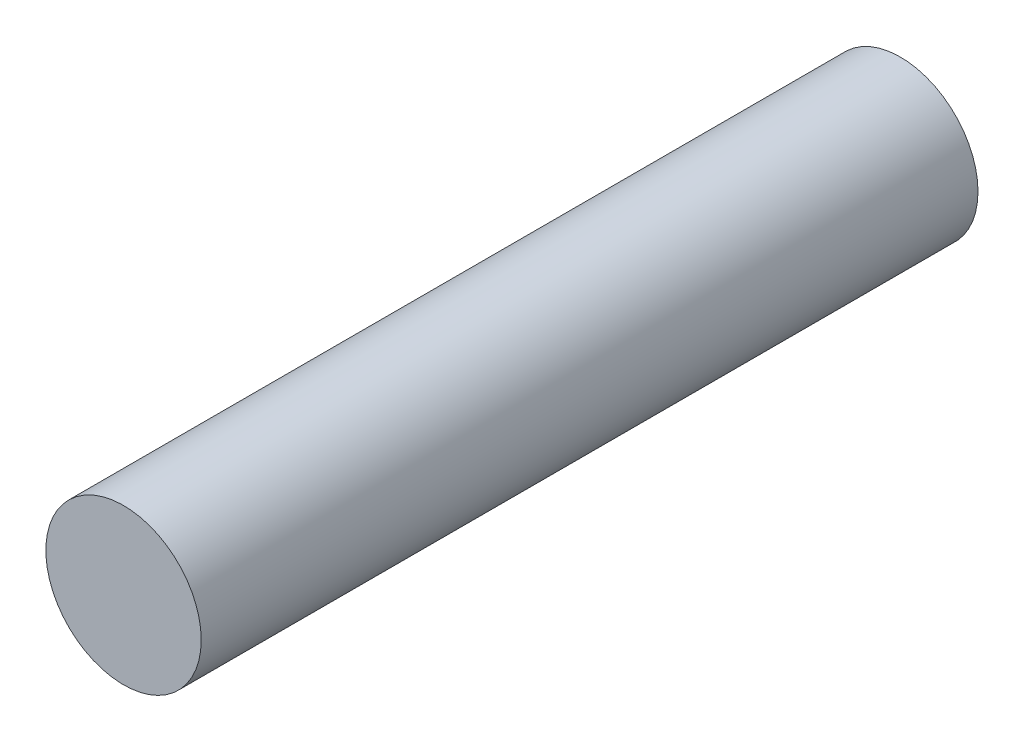
SolidWorks part; units mm, degrees
ref_plane "Front Plane" through (0, 0, 0) normal (0, 0, 1) x (1, 0, 0)
ref_plane "Top Plane" through (0, 0, 0) normal (0, 1, 0) x (1, 0, 0)
ref_plane "Right Plane" through (0, 0, 0) normal (1, 0, 0) x (0, 0, -1)
sketch "Sketch1" plane through (0, 0, 0) normal (0, 0, 1) x (1, 0, 0)
  circle A0 centre (0, 0) radius 1.5
  dimension "D1" = 3
extrude "Boss-Extrude1" add sketch "Sketch1" along normal blind 15
